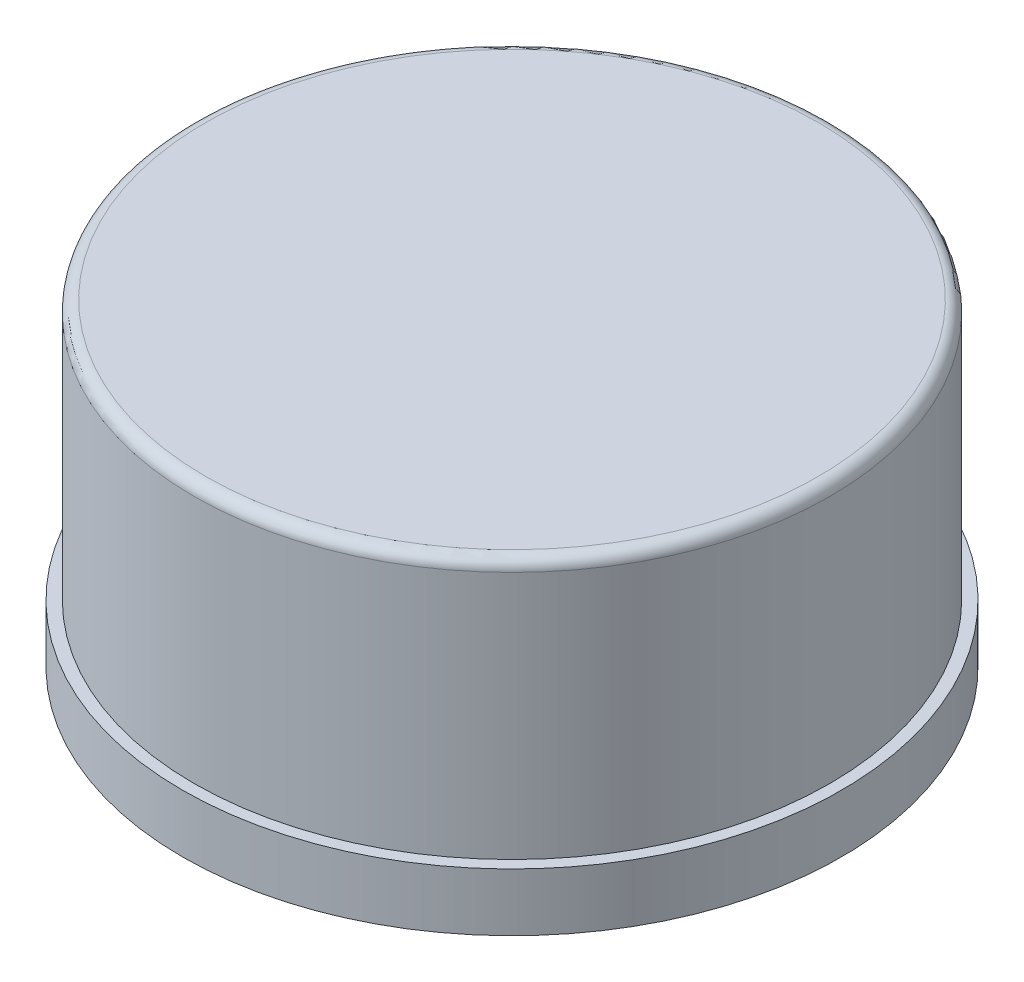
SolidWorks part; units mm, degrees
ref_plane "Front Plane" through (0, 0, 0) normal (0, 0, 1) x (1, 0, 0)
ref_plane "Top Plane" through (0, 0, 0) normal (0, 1, 0) x (1, 0, 0)
ref_plane "Right Plane" through (0, 0, 0) normal (1, 0, 0) x (0, 0, -1)
sketch "Sketch7" plane through (0, 0, 0) normal (0, 1, 0) x (1, 0, 0)
  circle A0 centre (0, 0) radius 5.7
  dimension "D1" = 11.4
extrude "Boss-Extrude2" add sketch "Sketch7" along normal blind 1
sketch "Sketch8" plane through (0, 1, 0) normal (0, 1, 0) x (1, 0, 0)
  circle A0 centre (0, 0) radius 5.5
  dimension "D1" = 11
extrude "Boss-Extrude3" add sketch "Sketch8" along normal blind 4.5 contours A0
fillet "Fillet4" radius 0.2 1 edges at (0, 5.5, 5.5)
sketch "Sketch9" plane through (0, 0, 0) normal (0, -1, 0) x (1, 0, 0)
  line L1 (2.5, -2.5) -> (-2.5, -2.5)
  line L2 (2.5, -2.5) -> (2.5, 2.5)
  line L3 (2.5, 2.5) -> (-2.5, 2.5)
  line L4 (-2.5, -2.5) -> (-2.5, 2.5)
  line L5 (2.5, -2.5) -> (-2.5, 2.5) construction
  line L6 (2.5, 2.5) -> (-2.5, -2.5) construction
  point P0 (0, 0)
  dimension "D1" = 5
  dimension "D2" = 5
extrude "Boss-Extrude4" add sketch "Sketch9" along normal blind 0.1 contours L3 L4 L1 L2
shell "Shell3" thickness 0.6
